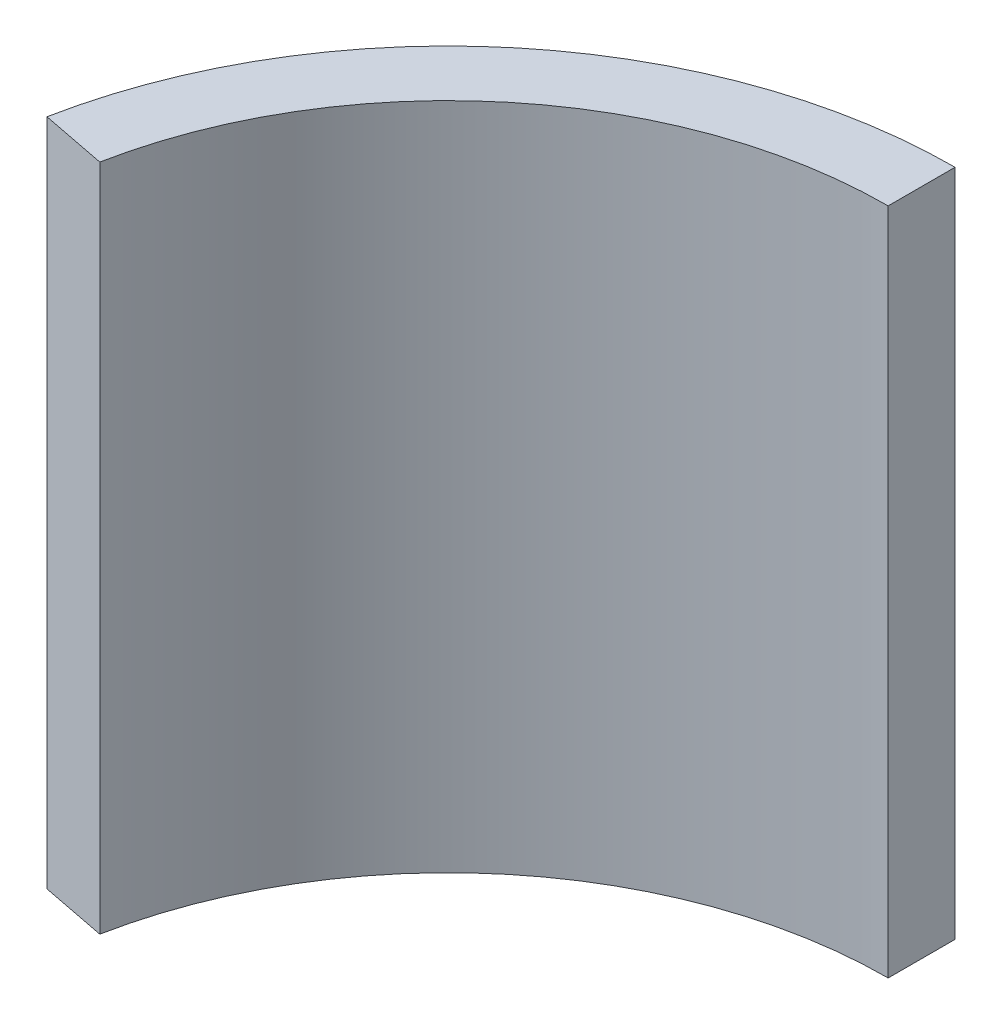
SolidWorks part; units mm, degrees
ref_plane "Front Plane" through (0, 0, 0) normal (0, 0, 1) x (1, 0, 0)
ref_plane "Top Plane" through (0, 0, 0) normal (0, 1, 0) x (1, 0, 0)
ref_plane "Right Plane" through (0, 0, 0) normal (1, 0, 0) x (0, 0, -1)
sketch "RevolveSketch" plane through (0, 0, 0) normal (1, 0, 0) x (0, 0, -1)
  line L0 (11, -9) -> (11, 15)
  line L1 (-6, -18) -> (-6, 26) construction
revolve "ThinBossRevolve" add sketch "RevolveSketch" angle 79 about L1
